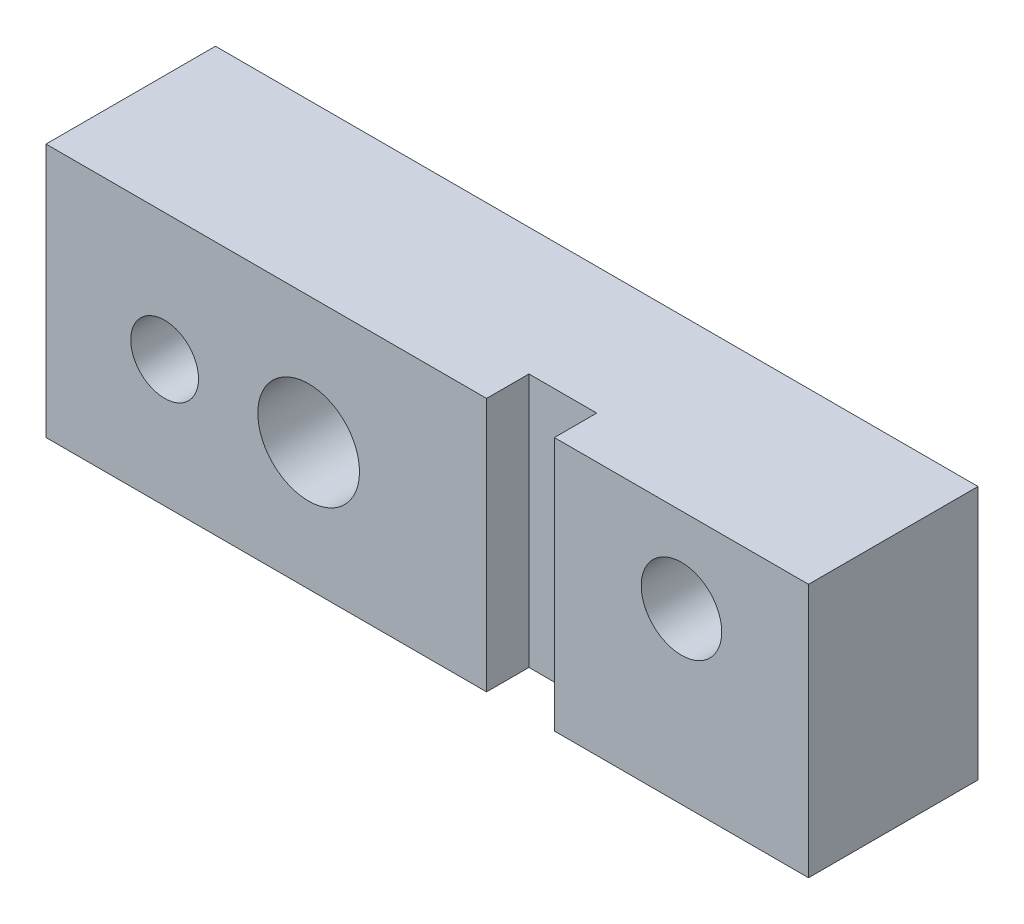
SolidWorks part; units mm, degrees
ref_plane "Спереди" through (0, 0, 0) normal (0, 0, 1) x (1, 0, 0)
ref_plane "Сверху" through (0, 0, 0) normal (0, 1, 0) x (1, 0, 0)
ref_plane "Справа" through (0, 0, 0) normal (1, 0, 0) x (0, 0, -1)
sketch "Эскиз1" plane through (0, 0, 0) normal (0, 0, 1) x (1, 0, 0)
  line L1 (0, 0) -> (90, 0)
  line L2 (0, 0) -> (0, 30)
  line L3 (0, 30) -> (90, 30)
  line L4 (90, 0) -> (90, 30)
  dimension "D1" = 30
  dimension "D2" = 90
extrude "Бобышка-Вытянуть1" add sketch "Эскиз1" against normal blind 20
sketch "Эскиз2" plane through (0, 0, 0) normal (0, 0, 1) x (1, 0, 0)
  line L0 (90, 30) -> (0, 30) construction
  line L1 (52, 30) -> (60, 30)
  line L2 (52, 30) -> (52, 0)
  line L3 (52, 0) -> (60, 0)
  line L4 (60, 30) -> (60, 0)
  line L5 (0, 0) -> (90, 0) construction
  dimension "D1" = 52
  dimension "D2" = 8
extrude "Вырез-Вытянуть1" cut sketch "Эскиз2" against normal blind 5
sketch "Эскиз8" plane through (0, 0, 0) normal (0, 0, 1) x (1, 0, 0)
  circle A0 centre (75, 20) radius 4.75
  dimension "D3" = 9.5
  dimension "D1" = 20
  dimension "D2" = 15
extrude "Вырез-Вытянуть4" cut sketch "Эскиз8" against normal through all
ref_plane "Плоскость4" through (0, 15, 0) normal (0, 1, 0) x (1, 0, 0)
sketch "Эскиз5" plane through (0, 15, 0) normal (0, 1, 0) x (1, 0, 0)
  line L0 (31, 0) -> (31, 20) construction
  line L1 (52, 0) -> (0, 0) construction
  line L2 (90, 20) -> (0, 20) construction
  line L3 (31, 0) -> (37, 0)
  line L4 (37, 0) -> (37, 12)
  line L5 (37, 12) -> (34, 12)
  line L6 (34, 12) -> (34, 20)
  line L7 (34, 20) -> (31, 20)
  line L8 (31, 20) -> (31, 0)
  dimension "D1" = 21
  dimension "D2" = 6
  dimension "D3" = 3
  dimension "D4" = 12
revolve "Вырез-Повернуть1" cut sketch "Эскиз5" angle 360 about L0
sketch "Эскиз6" plane through (0, 15, 0) normal (0, 1, 0) x (1, 0, 0)
  line L0 (14, 0) -> (14, 20) construction
  line L1 (52, 0) -> (0, 0) construction
  line L2 (90, 20) -> (0, 20) construction
  line L3 (14, 0) -> (18, 0)
  line L4 (18, 0) -> (18, 10)
  line L5 (18, 10) -> (14, 12.3094)
  line L6 (14, 12.3094) -> (14, 0)
  dimension "D1" = 14
  dimension "D2" = 60
  dimension "D3" = 10
  dimension "D4" = 4
revolve "Вырез-Повернуть2" cut sketch "Эскиз6" angle 360 about L0
